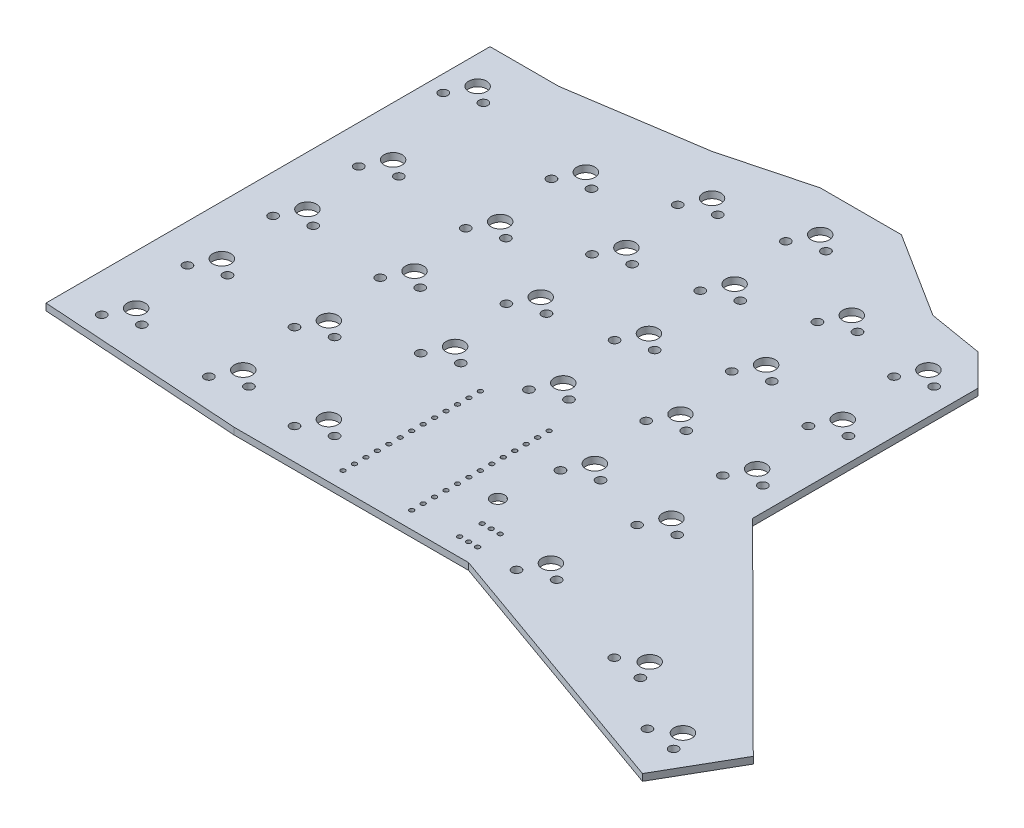
SolidWorks part; units mm, degrees
ref_plane "Front Plane" through (0, 0, 0) normal (0, 0, 1) x (1, 0, 0)
ref_plane "Top Plane" through (0, 0, 0) normal (0, 1, 0) x (1, 0, 0)
ref_plane "Right Plane" through (0, 0, 0) normal (1, 0, 0) x (0, 0, -1)
sketch "Main" plane through (0, 0, 0) normal (0, 1, 0) x (1, 0, 0)
  line L0 (6.46, 3.92) -> (12.81, 6.46) construction
  line L1 (0, 0) -> (18, 0) construction
  line L2 (0, 0) -> (0, 18) construction
  line L3 (0, 18) -> (18, 18) construction
  line L4 (18, 0) -> (18, 18) construction
  line L5 (2, 16) -> (16, 16)
  line L6 (2, 16) -> (2, 2)
  line L7 (2, 2) -> (16, 2)
  line L8 (16, 16) -> (16, 2)
  line L18 (9, 9) -> (6.46, 3.92) construction
  line L20 (9, 9) -> (12.81, 6.46) construction
  line L22 (25.46, 12.92) -> (31.81, 15.46) construction
  line L23 (19, 9) -> (37, 9) construction
  line L24 (19, 9) -> (19, 27) construction
  line L25 (19, 27) -> (37, 27) construction
  line L26 (37, 9) -> (37, 27) construction
  line L27 (21, 25) -> (35, 25)
  line L28 (21, 25) -> (21, 11)
  line L29 (21, 11) -> (35, 11)
  line L30 (35, 25) -> (35, 11)
  line L31 (28, 18) -> (25.46, 12.92) construction
  line L32 (28, 18) -> (31.81, 15.46) construction
  line L33 (44.46, 17.92) -> (50.81, 20.46) construction
  line L34 (38, 14) -> (56, 14) construction
  line L35 (38, 14) -> (38, 32) construction
  line L36 (38, 32) -> (56, 32) construction
  line L37 (56, 14) -> (56, 32) construction
  line L38 (40, 30) -> (54, 30)
  line L39 (40, 30) -> (40, 16)
  line L40 (40, 16) -> (54, 16)
  line L41 (54, 30) -> (54, 16)
  line L42 (47, 23) -> (44.46, 17.92) construction
  line L43 (47, 23) -> (50.81, 20.46) construction
  line L44 (63.46, 5.92) -> (69.81, 8.46) construction
  line L45 (57, 2) -> (75, 2) construction
  line L46 (57, 2) -> (57, 20) construction
  line L47 (57, 20) -> (75, 20) construction
  line L48 (75, 2) -> (75, 20) construction
  line L49 (59, 18) -> (73, 18)
  line L50 (59, 18) -> (59, 4)
  line L51 (59, 4) -> (73, 4)
  line L52 (73, 18) -> (73, 4)
  line L53 (66, 11) -> (63.46, 5.92) construction
  line L54 (66, 11) -> (69.81, 8.46) construction
  line L55 (82.46, 3.92) -> (88.81, 6.46) construction
  line L56 (76, 0) -> (94, 0) construction
  line L57 (76, 0) -> (76, 18) construction
  line L58 (76, 18) -> (94, 18) construction
  line L59 (94, 0) -> (94, 18) construction
  line L60 (78, 16) -> (92, 16)
  line L61 (78, 16) -> (78, 2)
  line L62 (78, 2) -> (92, 2)
  line L63 (92, 16) -> (92, 2)
  line L64 (85, 9) -> (82.46, 3.92) construction
  line L65 (85, 9) -> (88.81, 6.46) construction
  line L88 (2, -3) -> (16, -3)
  line L89 (2, -3) -> (2, -17)
  line L90 (2, -17) -> (16, -17)
  line L91 (16, -3) -> (16, -17)
  line L92 (21, 6) -> (35, 6)
  line L93 (21, 6) -> (21, -8)
  line L94 (21, -8) -> (35, -8)
  line L95 (35, 6) -> (35, -8)
  line L96 (40, 11) -> (54, 11)
  line L97 (40, 11) -> (40, -3)
  line L98 (40, -3) -> (54, -3)
  line L99 (54, 11) -> (54, -3)
  line L100 (59, -1) -> (73, -1)
  line L101 (59, -1) -> (59, -15)
  line L102 (59, -15) -> (73, -15)
  line L103 (73, -1) -> (73, -15)
  line L104 (78, -3) -> (92, -3)
  line L105 (78, -3) -> (78, -17)
  line L106 (78, -17) -> (92, -17)
  line L107 (92, -3) -> (92, -17)
  line L116 (6.46, -15.08) -> (12.81, -12.54) construction
  line L117 (0, -19) -> (18, -19) construction
  line L118 (0, -19) -> (0, -1) construction
  line L119 (0, -1) -> (18, -1) construction
  line L120 (18, -19) -> (18, -1) construction
  line L121 (9, -10) -> (6.46, -15.08) construction
  line L122 (9, -10) -> (12.81, -12.54) construction
  line L123 (25.46, -6.08) -> (31.81, -3.54) construction
  line L124 (19, -10) -> (37, -10) construction
  line L125 (19, -10) -> (19, 8) construction
  line L126 (19, 8) -> (37, 8) construction
  line L127 (37, -10) -> (37, 8) construction
  line L128 (28, -1) -> (25.46, -6.08) construction
  line L129 (28, -1) -> (31.81, -3.54) construction
  line L130 (44.46, -1.08) -> (50.81, 1.46) construction
  line L131 (38, -5) -> (56, -5) construction
  line L132 (38, -5) -> (38, 13) construction
  line L133 (38, 13) -> (56, 13) construction
  line L134 (56, -5) -> (56, 13) construction
  line L135 (47, 4) -> (44.46, -1.08) construction
  line L136 (47, 4) -> (50.81, 1.46) construction
  line L137 (63.46, -13.08) -> (69.81, -10.54) construction
  line L138 (57, -17) -> (75, -17) construction
  line L139 (57, -17) -> (57, 1) construction
  line L140 (57, 1) -> (75, 1) construction
  line L141 (75, -17) -> (75, 1) construction
  line L142 (66, -8) -> (63.46, -13.08) construction
  line L143 (66, -8) -> (69.81, -10.54) construction
  line L144 (82.46, -15.08) -> (88.81, -12.54) construction
  line L145 (76, -19) -> (94, -19) construction
  line L146 (76, -19) -> (76, -1) construction
  line L147 (76, -1) -> (94, -1) construction
  line L148 (94, -19) -> (94, -1) construction
  line L149 (85, -10) -> (82.46, -15.08) construction
  line L150 (85, -10) -> (88.81, -12.54) construction
  line L165 (2, -22) -> (16, -22)
  line L166 (2, -22) -> (2, -36)
  line L167 (2, -36) -> (16, -36)
  line L168 (16, -22) -> (16, -36)
  line L169 (21, -13) -> (35, -13)
  line L170 (21, -13) -> (21, -27)
  line L171 (21, -27) -> (35, -27)
  line L172 (35, -13) -> (35, -27)
  line L173 (40, -8) -> (54, -8)
  line L174 (40, -8) -> (40, -22)
  line L175 (40, -22) -> (54, -22)
  line L176 (54, -8) -> (54, -22)
  line L177 (59, -20) -> (73, -20)
  line L178 (59, -20) -> (59, -34)
  line L179 (59, -34) -> (73, -34)
  line L180 (73, -20) -> (73, -34)
  line L181 (78, -22) -> (92, -22)
  line L182 (78, -22) -> (78, -36)
  line L183 (78, -36) -> (92, -36)
  line L184 (92, -22) -> (92, -36)
  line L193 (6.46, -34.08) -> (12.81, -31.54) construction
  line L194 (0, -38) -> (18, -38) construction
  line L195 (0, -38) -> (0, -20) construction
  line L196 (0, -20) -> (18, -20) construction
  line L197 (18, -38) -> (18, -20) construction
  line L198 (9, -29) -> (6.46, -34.08) construction
  line L199 (9, -29) -> (12.81, -31.54) construction
  line L200 (25.46, -25.08) -> (31.81, -22.54) construction
  line L201 (19, -29) -> (37, -29) construction
  line L202 (19, -29) -> (19, -11) construction
  line L203 (19, -11) -> (37, -11) construction
  line L204 (37, -29) -> (37, -11) construction
  line L205 (28, -20) -> (25.46, -25.08) construction
  line L206 (28, -20) -> (31.81, -22.54) construction
  line L207 (44.46, -20.08) -> (50.81, -17.54) construction
  line L208 (38, -24) -> (56, -24) construction
  line L209 (38, -24) -> (38, -6) construction
  line L210 (38, -6) -> (56, -6) construction
  line L211 (56, -24) -> (56, -6) construction
  line L212 (47, -15) -> (44.46, -20.08) construction
  line L213 (47, -15) -> (50.81, -17.54) construction
  line L214 (63.46, -32.08) -> (69.81, -29.54) construction
  line L215 (57, -36) -> (75, -36) construction
  line L216 (57, -36) -> (57, -18) construction
  line L217 (57, -18) -> (75, -18) construction
  line L218 (75, -36) -> (75, -18) construction
  line L219 (66, -27) -> (63.46, -32.08) construction
  line L220 (66, -27) -> (69.81, -29.54) construction
  line L221 (82.46, -34.08) -> (88.81, -31.54) construction
  line L222 (76, -38) -> (94, -38) construction
  line L223 (76, -38) -> (76, -20) construction
  line L224 (76, -20) -> (94, -20) construction
  line L225 (94, -38) -> (94, -20) construction
  line L226 (85, -29) -> (82.46, -34.08) construction
  line L227 (85, -29) -> (88.81, -31.54) construction
  line L242 (2, -41) -> (16, -41)
  line L243 (2, -41) -> (2, -55)
  line L244 (2, -55) -> (16, -55)
  line L245 (16, -41) -> (16, -55)
  line L246 (21, -32) -> (35, -32)
  line L247 (21, -32) -> (21, -46)
  line L248 (21, -46) -> (35, -46)
  line L249 (35, -32) -> (35, -46)
  line L250 (40, -27) -> (54, -27)
  line L251 (40, -27) -> (40, -41)
  line L252 (40, -41) -> (54, -41)
  line L253 (54, -27) -> (54, -41)
  line L254 (59, -39) -> (73, -39)
  line L255 (59, -39) -> (59, -53)
  line L256 (59, -53) -> (73, -53)
  line L257 (73, -39) -> (73, -53)
  line L258 (78, -41) -> (92, -41)
  line L259 (78, -41) -> (78, -55)
  line L260 (78, -55) -> (92, -55)
  line L261 (92, -41) -> (92, -55)
  line L270 (6.46, -53.08) -> (12.81, -50.54) construction
  line L271 (0, -57) -> (18, -57) construction
  line L272 (0, -57) -> (0, -39) construction
  line L273 (0, -39) -> (18, -39) construction
  line L274 (18, -57) -> (18, -39) construction
  line L275 (9, -48) -> (6.46, -53.08) construction
  line L276 (9, -48) -> (12.81, -50.54) construction
  line L277 (25.46, -44.08) -> (31.81, -41.54) construction
  line L278 (19, -48) -> (37, -48) construction
  line L279 (19, -48) -> (19, -30) construction
  line L280 (19, -30) -> (37, -30) construction
  line L281 (37, -48) -> (37, -30) construction
  line L282 (28, -39) -> (25.46, -44.08) construction
  line L283 (28, -39) -> (31.81, -41.54) construction
  line L284 (44.46, -39.08) -> (50.81, -36.54) construction
  line L285 (38, -43) -> (56, -43) construction
  line L286 (38, -43) -> (38, -25) construction
  line L287 (38, -25) -> (56, -25) construction
  line L288 (56, -43) -> (56, -25) construction
  line L289 (47, -34) -> (44.46, -39.08) construction
  line L290 (47, -34) -> (50.81, -36.54) construction
  line L291 (63.46, -51.08) -> (69.81, -48.54) construction
  line L292 (57, -55) -> (75, -55) construction
  line L293 (57, -55) -> (57, -37) construction
  line L294 (57, -37) -> (75, -37) construction
  line L295 (75, -55) -> (75, -37) construction
  line L296 (66, -46) -> (63.46, -51.08) construction
  line L297 (66, -46) -> (69.81, -48.54) construction
  line L298 (82.46, -53.08) -> (88.81, -50.54) construction
  line L299 (76, -57) -> (94, -57) construction
  line L300 (76, -57) -> (76, -39) construction
  line L301 (76, -39) -> (94, -39) construction
  line L302 (94, -57) -> (94, -39) construction
  line L303 (85, -48) -> (82.46, -53.08) construction
  line L304 (85, -48) -> (88.81, -50.54) construction
  line L312 (6.46, -72.08) -> (12.81, -69.54) construction
  line L313 (0, -76) -> (18, -76) construction
  line L314 (0, -76) -> (0, -58) construction
  line L315 (0, -58) -> (18, -58) construction
  line L316 (18, -76) -> (18, -58) construction
  line L317 (2, -60) -> (16, -60)
  line L318 (2, -60) -> (2, -74)
  line L323 (21, -60) -> (35, -60)
  line L324 (21, -60) -> (21, -74)
  line L325 (21, -74) -> (35, -74)
  line L326 (35, -60) -> (35, -74)
  line L327 (25.46, -72.08) -> (31.81, -69.54) construction
  line L328 (19, -76) -> (37, -76) construction
  line L329 (19, -76) -> (19, -58) construction
  line L330 (-22.04, 8.42) -> (-15.69, 10.96) construction
  line L331 (-28.5, 4.5) -> (-10.5, 4.5) construction
  line L332 (-28.5, 4.5) -> (-28.5, 22.5) construction
  line L333 (-28.5, 22.5) -> (-10.5, 22.5) construction
  line L334 (-10.5, 4.5) -> (-10.5, 22.5) construction
  line L335 (-26.5, 20.5) -> (-12.5, 20.5)
  line L336 (-26.5, 20.5) -> (-26.5, 6.5)
  line L337 (-26.5, 6.5) -> (-12.5, 6.5)
  line L338 (-12.5, 20.5) -> (-12.5, 6.5)
  line L339 (-19.5, 13.5) -> (-22.04, 8.42) construction
  line L340 (-19.5, 13.5) -> (-15.69, 10.96) construction
  line L341 (-21.75, -41) -> (-7.75, -41)
  line L342 (-21.75, -41) -> (-21.75, -55)
  line L343 (-21.75, -55) -> (-7.75, -55)
  line L344 (-7.75, -41) -> (-7.75, -55)
  line L345 (-17.29, -53.08) -> (-10.94, -50.54) construction
  line L346 (-28.5, -57) -> (-1, -57) construction
  line L347 (-28.5, -57) -> (-28.5, -39) construction
  line L348 (-28.5, -39) -> (-1, -39) construction
  line L349 (-1, -57) -> (-1, -39) construction
  line L350 (-14.75, -48) -> (-17.29, -53.08) construction
  line L351 (-14.75, -48) -> (-10.94, -50.54) construction
  line L352 (-21.75, -22) -> (-7.75, -22)
  line L353 (-21.75, -22) -> (-21.75, -36)
  line L354 (2, -74) -> (16, -74)
  line L355 (16, -60) -> (16, -74)
  line L356 (9, -67) -> (6.46, -72.08) construction
  line L357 (9, -67) -> (12.81, -69.54) construction
  line L358 (-17.29, -72.08) -> (-10.94, -69.54) construction
  line L359 (-28.5, -76) -> (-1, -76) construction
  line L360 (-28.5, -76) -> (-28.5, -58) construction
  line L361 (-28.5, -58) -> (-1, -58) construction
  line L362 (-1, -76) -> (-1, -58) construction
  line L363 (-21.75, -60) -> (-7.75, -60)
  line L364 (-21.75, -60) -> (-21.75, -74)
  line L365 (-21.75, -74) -> (-7.75, -74)
  line L366 (-7.75, -60) -> (-7.75, -74)
  line L367 (-14.75, -67) -> (-17.29, -72.08) construction
  line L368 (-14.75, -67) -> (-10.94, -69.54) construction
  line L369 (-21.75, -36) -> (-7.75, -36)
  line L370 (-7.75, -22) -> (-7.75, -36)
  line L371 (-17.29, -34.08) -> (-10.94, -31.54) construction
  line L372 (-28.5, -38) -> (-1, -38) construction
  line L373 (-28.5, -38) -> (-28.5, -20) construction
  line L374 (-28.5, -20) -> (-1, -20) construction
  line L375 (-1, -38) -> (-1, -20) construction
  line L376 (-14.75, -29) -> (-17.29, -34.08) construction
  line L377 (-14.75, -29) -> (-10.94, -31.54) construction
  line L378 (-21.75, -3) -> (-7.75, -3)
  line L379 (-21.75, -3) -> (-21.75, -17)
  line L380 (-21.75, -17) -> (-7.75, -17)
  line L381 (-7.75, -3) -> (-7.75, -17)
  line L382 (-17.29, -15.08) -> (-10.94, -12.54) construction
  line L383 (-28.5, -19) -> (-1, -19) construction
  line L384 (-28.5, -19) -> (-28.5, -1) construction
  line L385 (-28.5, -1) -> (-1, -1) construction
  line L386 (-1, -19) -> (-1, -1) construction
  line L387 (-14.75, -10) -> (-17.29, -15.08) construction
  line L388 (-14.75, -10) -> (-10.94, -12.54) construction
  line L393 (109.2068, -61.578) -> (124.8116, -70.5498) construction
  line L394 (109.2068, -61.578) -> (95.5, -85.4186) construction
  line L398 (124.8116, -70.5498) -> (111.1047, -94.3903) construction
  line L402 (77.71, -75.08) -> (84.06, -72.54) construction
  line L403 (66.5, -79) -> (94, -79) construction
  line L404 (66.5, -79) -> (66.5, -61) construction
  line L405 (66.5, -61) -> (94, -61) construction
  line L406 (94, -79) -> (94, -61) construction
  line L407 (73.25, -63) -> (87.25, -63)
  line L408 (73.25, -63) -> (73.25, -77)
  line L409 (73.25, -77) -> (87.25, -77)
  line L410 (87.25, -63) -> (87.25, -77)
  line L411 (80.25, -70) -> (77.71, -75.08) construction
  line L412 (80.25, -70) -> (84.06, -72.54) construction
  line L413 (95.5, -85.4186) -> (111.1047, -94.3903) construction
  line L414 (95.5, -85.4186) -> (124.8116, -70.5498) construction
  line L415 (80.25, -130) -> (110.1558, -77.9842) construction
  line L416 (107.5763, -68.4267) -> (119.7133, -75.4047)
  line L417 (107.5763, -68.4267) -> (100.5983, -80.5637)
  line L418 (119.7133, -75.4047) -> (112.7353, -87.5417)
  line L419 (100.5983, -80.5637) -> (112.7353, -87.5417)
  line L420 (107.5763, -68.4267) -> (112.7353, -87.5417) construction
  line L421 (105.4217, -81.1221) -> (110.1558, -77.9842) construction
  line L422 (110.1558, -77.9842) -> (112.1927, -82.0853) construction
  line L423 (112.1927, -82.0853) -> (105.4217, -81.1221) construction
  line L424 (126.5454, -71.5466) -> (142.1502, -80.5184) construction
  line L425 (126.5454, -71.5466) -> (112.8386, -95.3872) construction
  line L426 (142.1502, -80.5184) -> (128.4433, -104.3589) construction
  line L427 (112.8386, -95.3872) -> (128.4433, -104.3589) construction
  line L428 (112.8386, -95.3872) -> (142.1502, -80.5184) construction
  line L430 (124.9149, -78.3953) -> (137.0519, -85.3733)
  line L431 (124.9149, -78.3953) -> (117.9369, -90.5323)
  line L432 (137.0519, -85.3733) -> (130.0739, -97.5103)
  line L433 (117.9369, -90.5323) -> (130.0739, -97.5103)
  line L434 (124.9149, -78.3953) -> (130.0739, -97.5103) construction
  line L435 (122.7603, -91.0907) -> (127.4944, -87.9528) construction
  line L436 (127.4944, -87.9528) -> (129.5313, -92.0539) construction
  line L437 (129.5313, -92.0539) -> (122.7603, -91.0907) construction
  line L448 (19, -58) -> (37, -58) construction
  line L449 (37, -76) -> (37, -58) construction
  line L450 (28, -67) -> (25.46, -72.08) construction
  line L451 (28, -67) -> (31.81, -69.54) construction
  circle A0 centre (9, 9) radius 2 construction
  circle A1 centre (6.46, 3.92) radius 1.5 construction
  circle A2 centre (12.81, 6.46) radius 1.5 construction
  circle A6 centre (28, 18) radius 2 construction
  circle A7 centre (25.46, 12.92) radius 1.5 construction
  circle A8 centre (31.81, 15.46) radius 1.5 construction
  circle A9 centre (47, 23) radius 2 construction
  circle A10 centre (44.46, 17.92) radius 1.5 construction
  circle A11 centre (50.81, 20.46) radius 1.5 construction
  circle A12 centre (66, 11) radius 2 construction
  circle A13 centre (63.46, 5.92) radius 1.5 construction
  circle A14 centre (69.81, 8.46) radius 1.5 construction
  circle A15 centre (85, 9) radius 2 construction
  circle A16 centre (82.46, 3.92) radius 1.5 construction
  circle A17 centre (88.81, 6.46) radius 1.5 construction
  circle A24 centre (9, -10) radius 2 construction
  circle A25 centre (6.46, -15.08) radius 1.5 construction
  circle A26 centre (12.81, -12.54) radius 1.5 construction
  circle A27 centre (28, -1) radius 2 construction
  circle A28 centre (25.46, -6.08) radius 1.5 construction
  circle A29 centre (31.81, -3.54) radius 1.5 construction
  circle A30 centre (47, 4) radius 2 construction
  circle A31 centre (44.46, -1.08) radius 1.5 construction
  circle A32 centre (50.81, 1.46) radius 1.5 construction
  circle A33 centre (66, -8) radius 2 construction
  circle A34 centre (63.46, -13.08) radius 1.5 construction
  circle A35 centre (69.81, -10.54) radius 1.5 construction
  circle A36 centre (85, -10) radius 2 construction
  circle A37 centre (82.46, -15.08) radius 1.5 construction
  circle A38 centre (88.81, -12.54) radius 1.5 construction
  circle A45 centre (9, -29) radius 2 construction
  circle A46 centre (6.46, -34.08) radius 1.5 construction
  circle A47 centre (12.81, -31.54) radius 1.5 construction
  circle A48 centre (28, -20) radius 2 construction
  circle A49 centre (25.46, -25.08) radius 1.5 construction
  circle A50 centre (31.81, -22.54) radius 1.5 construction
  circle A51 centre (47, -15) radius 2 construction
  circle A52 centre (44.46, -20.08) radius 1.5 construction
  circle A53 centre (50.81, -17.54) radius 1.5 construction
  circle A54 centre (66, -27) radius 2 construction
  circle A55 centre (63.46, -32.08) radius 1.5 construction
  circle A56 centre (69.81, -29.54) radius 1.5 construction
  circle A57 centre (85, -29) radius 2 construction
  circle A58 centre (82.46, -34.08) radius 1.5 construction
  circle A59 centre (88.81, -31.54) radius 1.5 construction
  circle A63 centre (9, -67) radius 2 construction
  circle A64 centre (6.46, -72.08) radius 1.5 construction
  circle A65 centre (12.81, -69.54) radius 1.5 construction
  circle A66 centre (9, -48) radius 2 construction
  circle A67 centre (6.46, -53.08) radius 1.5 construction
  circle A68 centre (12.81, -50.54) radius 1.5 construction
  circle A69 centre (28, -39) radius 2 construction
  circle A70 centre (25.46, -44.08) radius 1.5 construction
  circle A71 centre (31.81, -41.54) radius 1.5 construction
  circle A72 centre (47, -34) radius 2 construction
  circle A73 centre (44.46, -39.08) radius 1.5 construction
  circle A74 centre (50.81, -36.54) radius 1.5 construction
  circle A75 centre (66, -46) radius 2 construction
  circle A76 centre (63.46, -51.08) radius 1.5 construction
  circle A77 centre (69.81, -48.54) radius 1.5 construction
  circle A78 centre (85, -48) radius 2 construction
  circle A79 centre (82.46, -53.08) radius 1.5 construction
  circle A80 centre (88.81, -50.54) radius 1.5 construction
  circle A81 centre (-14.75, -67) radius 2 construction
  circle A82 centre (-17.29, -72.08) radius 1.5 construction
  circle A83 centre (-10.94, -69.54) radius 1.5 construction
  circle A84 centre (28, -67) radius 2 construction
  circle A85 centre (25.46, -72.08) radius 1.5 construction
  circle A86 centre (31.81, -69.54) radius 1.5 construction
  circle A87 centre (-19.5, 13.5) radius 2 construction
  circle A88 centre (-22.04, 8.42) radius 1.5 construction
  circle A89 centre (-15.69, 10.96) radius 1.5 construction
  circle A90 centre (-14.75, -48) radius 2 construction
  circle A91 centre (-17.29, -53.08) radius 1.5 construction
  circle A92 centre (-10.94, -50.54) radius 1.5 construction
  circle A93 centre (-14.75, -29) radius 2 construction
  circle A94 centre (-17.29, -34.08) radius 1.5 construction
  circle A95 centre (-10.94, -31.54) radius 1.5 construction
  circle A96 centre (-14.75, -10) radius 2 construction
  circle A97 centre (-17.29, -15.08) radius 1.5 construction
  circle A98 centre (-10.94, -12.54) radius 1.5 construction
  circle A102 centre (80.25, -70) radius 2 construction
  circle A103 centre (77.71, -75.08) radius 1.5 construction
  circle A104 centre (84.06, -72.54) radius 1.5 construction
  circle A105 centre (80.25, -130) radius 60 construction
  circle A106 centre (110.1558, -77.9842) radius 2 construction
  circle A107 centre (105.4217, -81.1221) radius 1.5 construction
  circle A108 centre (112.1927, -82.0853) radius 1.5 construction
  circle A109 centre (127.4944, -87.9528) radius 2 construction
  circle A110 centre (122.7603, -91.0907) radius 1.5 construction
  circle A111 centre (129.5313, -92.0539) radius 1.5 construction
  point P9 (9, 16)
  point P10 (9, 18)
  point P11 (2, 9)
  point P12 (0, 9)
  point P30 (28, 25)
  point P31 (28, 27)
  point P32 (21, 18)
  point P33 (19, 18)
  point P46 (47, 30)
  point P47 (47, 32)
  point P48 (40, 23)
  point P49 (38, 23)
  point P64 (66, 18)
  point P65 (66, 20)
  point P66 (59, 11)
  point P67 (57, 11)
  point P82 (85, 16)
  point P83 (85, 18)
  point P84 (78, 9)
  point P85 (76, 9)
  point P102 (9, -60)
  point P103 (9, -58)
  point P104 (2, -67)
  point P105 (0, -67)
  point P124 (-14.75, -60)
  point P125 (-14.75, -58)
  point P126 (-21.75, -67)
  point P127 (-28.5, -67)
  point P297 (-19.5, 20.5)
  point P298 (-19.5, 22.5)
  point P299 (-26.5, 13.5)
  point P300 (-28.5, 13.5)
  point P423 (103.3024, -89.9045)
  point P444 (80.25, -63)
  point P445 (80.25, -61)
  point P446 (73.25, -70)
  point P447 (66.5, -70)
  dimension "D6" = 4
  dimension "D7" = 3
  dimension "D10" = 1
  dimension "D11" = 12
  dimension "D21" = 9.5
  dimension "D22" = 1.5
  dimension "D26" = 120
  dimension "D38" = 21.8
  dimension "D1" = 18
  dimension "D2" = 14
  dimension "D3" = 3.81
  dimension "D4" = 2.54
  dimension "D5" = 2.54
  dimension "D8" = 1
  dimension "D9" = 5
  dimension "D12" = 1
  dimension "D13" = 9
  dimension "D14" = 1
  dimension "D15" = 2
  dimension "D16" = 2
  dimension "D17" = 27.5
  dimension "D18" = 1
  dimension "D20" = 1
  dimension "D24" = 1
  dimension "D25" = 8
  dimension "D27" = 2
  dimension "D28" = 5.08
  dimension "D29" = 2.54
  dimension "D30" = 2.54
  dimension "D31" = 2.54
  dimension "D32" = 2.54
  dimension "D33" = 2.54
  dimension "D34" = 2.54
  dimension "D35" = 2.54
  dimension "D36" = 2.54
  dimension "D37" = 21.8
  dimension "D19" = 4
  dimension "D23" = 4
sketch "Sketch1" plane through (0, 0, 0) normal (0, 1, 0) x (1, 0, 0)
  line L7 (87, 18) -> (94, 11)
  line L8 (115.2061, -91.2693) -> (124.1779, -75.6645) construction
  line L9 (76, 18) -> (94, 18) construction
  line L10 (94, 0) -> (94, 18) construction
  line L11 (66.5, -79) -> (94, -79) construction
  line L12 (115.2061, -91.2693) -> (130.8109, -100.241) construction
  line L14 (124.1779, -75.6645) -> (139.7826, -84.6363) construction
  line L18 (130.8109, -100.241) -> (139.7826, -84.6363)
  line L19 (115.2061, -91.2693) -> (139.7826, -84.6363) construction
  line L20 (124.1779, -75.6645) -> (130.8109, -100.241) construction
  line L23 (142.1502, -80.5184) -> (128.4433, -104.3589) construction
  line L27 (71, -79) -> (130.8109, -100.241)
  line L28 (139.7826, -84.6363) -> (94, -39)
  line L29 (94, -39) -> (94, 11)
  line L30 (87, 18) -> (75, 20)
  line L31 (75, 20) -> (56, 32)
  line L32 (56, 32) -> (38, 32)
  line L33 (38, 32) -> (19, 27)
  line L34 (19, 27) -> (-10.5, 22.5)
  line L35 (-10.5, 22.5) -> (-25.75, 22.5)
  line L38 (19, -79) -> (71, -79)
  line L167 (19, -76) -> (19, -58) construction
  line L168 (75, -55) -> (75, -37) construction
  line L169 (-28.5, -76) -> (-1, -76) construction
  line L174 (-23.75, -58) -> (-5.75, -58) construction
  line L175 (-23.75, -58) -> (-23.75, -76) construction
  line L176 (-23.75, -76) -> (-5.75, -76) construction
  line L177 (-5.75, -58) -> (-5.75, -76) construction
  line L178 (-23.75, -58) -> (-5.75, -76) construction
  line L179 (-23.75, -76) -> (-5.75, -58) construction
  line L181 (19, -79) -> (-25.75, -76)
  line L182 (-25.75, -76) -> (-25.75, 22.5)
  point P1 (127.4944, -87.9528)
  point P24 (-14.75, -67)
  dimension "D2" = 98.5203
  dimension "D7" = 64.643
  dimension "D8" = 7
  dimension "D3" = 42.8551
  dimension "D4" = 52
  dimension "D5" = 63.4706
  dimension "D6" = 18
  dimension "D9" = 7
  dimension "D10" = 22.4722
  dimension "D11" = 18
  dimension "D12" = 19.6469
  dimension "D13" = 29.8412
  dimension "D14" = 15.25
  dimension "D15" = 4
  dimension "D17" = 11
extrude "Main_plate" add sketch "Sketch1" against normal blind 1.5
sketch "Sketch3" plane through (0, 0, 0) normal (0, 1, 0) x (1, 0, 0)
  line L0 (80.25, -70) -> (77.71, -75.08) construction
  line L1 (112.8386, -95.3872) -> (142.1502, -80.5184) construction
  circle A0 centre (-19.5, 13.5) radius 2
  circle A1 centre (9, 9) radius 2
  circle A2 centre (28, 18) radius 2
  circle A3 centre (47, 23) radius 2
  circle A4 centre (66, 11) radius 2
  circle A5 centre (85, 9) radius 2
  circle A6 centre (-14.75, -10) radius 2
  circle A7 centre (9, -10) radius 2
  circle A8 centre (28, -1) radius 2
  circle A9 centre (47, 4) radius 2
  circle A10 centre (66, -8) radius 2
  circle A11 centre (85, -10) radius 2
  circle A12 centre (47, -15) radius 2
  circle A13 centre (-14.75, -29) radius 2
  circle A14 centre (-14.75, -48) radius 2
  circle A15 centre (-14.75, -67) radius 2
  circle A16 centre (9, -29) radius 2
  circle A17 centre (9, -48) radius 2
  circle A18 centre (9, -67) radius 2
  circle A19 centre (28, -67) radius 2
  circle A20 centre (28, -39) radius 2
  circle A21 centre (28, -20) radius 2
  circle A22 centre (47, -34) radius 2
  circle A23 centre (66, -27) radius 2
  circle A24 centre (85, -29) radius 2
  circle A25 centre (85, -48) radius 2
  circle A26 centre (66, -46) radius 2
  circle A27 centre (80.25, -70) radius 2
  circle A28 centre (110.1558, -77.9842) radius 2
  circle A29 centre (127.4944, -87.9528) radius 2
  circle A30 centre (-19.5, 13.5) radius 2 construction
extrude "Switch_holes_main" cut sketch "Sketch3" against normal through all
sketch "Sketch4" plane through (0, 0, 0) normal (0, 1, 0) x (1, 0, 0)
  circle A0 centre (-22.04, 8.42) radius 1
  circle A1 centre (-15.69, 10.96) radius 1
  circle A2 centre (-10.94, -12.54) radius 1
  circle A3 centre (-17.29, -15.08) radius 1
  circle A4 centre (-10.94, -31.54) radius 1
  circle A5 centre (-17.29, -34.08) radius 1
  circle A6 centre (-10.94, -50.54) radius 1
  circle A7 centre (-17.29, -53.08) radius 1
  circle A8 centre (-17.29, -72.08) radius 1
  circle A9 centre (-10.94, -69.54) radius 1
  circle A10 centre (6.46, -72.08) radius 1
  circle A11 centre (12.81, -69.54) radius 1
  circle A12 centre (25.46, -72.08) radius 1
  circle A13 centre (31.81, -69.54) radius 1
  circle A14 centre (6.46, -53.08) radius 1
  circle A15 centre (12.81, -50.54) radius 1
  circle A16 centre (6.46, -34.08) radius 1
  circle A17 centre (12.81, -31.54) radius 1
  circle A18 centre (25.46, -44.08) radius 1
  circle A19 centre (31.81, -41.54) radius 1
  circle A20 centre (25.46, -25.08) radius 1
  circle A21 centre (31.81, -22.54) radius 1
  circle A22 centre (6.46, -15.08) radius 1
  circle A23 centre (12.81, -12.54) radius 1
  circle A24 centre (6.46, 3.92) radius 1
  circle A25 centre (12.81, 6.46) radius 1
  circle A26 centre (25.46, 12.92) radius 1
  circle A27 centre (31.81, 15.46) radius 1
  circle A28 centre (25.46, -6.08) radius 1
  circle A29 centre (31.81, -3.54) radius 1
  circle A30 centre (44.46, 17.92) radius 1
  circle A31 centre (50.81, 20.46) radius 1
  circle A32 centre (44.46, -1.08) radius 1
  circle A33 centre (50.81, 1.46) radius 1
  circle A34 centre (44.46, -20.08) radius 1
  circle A35 centre (50.81, -17.54) radius 1
  circle A36 centre (44.46, -39.08) radius 1
  circle A37 centre (50.81, -36.54) radius 1
  circle A38 centre (69.81, 8.46) radius 1
  circle A39 centre (63.46, 5.92) radius 1
  circle A40 centre (82.46, 3.92) radius 1
  circle A41 centre (88.81, 6.46) radius 1
  circle A42 centre (69.81, -10.54) radius 1
  circle A43 centre (63.46, -13.08) radius 1
  circle A44 centre (82.46, -15.08) radius 1
  circle A45 centre (88.81, -12.54) radius 1
  circle A46 centre (63.46, -32.08) radius 1
  circle A47 centre (69.81, -29.54) radius 1
  circle A48 centre (63.46, -51.08) radius 1
  circle A49 centre (69.81, -48.54) radius 1
  circle A50 centre (82.46, -34.08) radius 1
  circle A51 centre (88.81, -31.54) radius 1
  circle A52 centre (88.81, -50.54) radius 1
  circle A53 centre (82.46, -53.08) radius 1
  circle A54 centre (77.71, -75.08) radius 1
  circle A55 centre (84.06, -72.54) radius 1
  circle A56 centre (105.4217, -81.1221) radius 1
  circle A57 centre (112.1927, -82.0853) radius 1
  circle A58 centre (122.7603, -91.0907) radius 1
  circle A59 centre (129.5313, -92.0539) radius 1
  dimension "D1" = 2
extrude "Switch_holes" cut sketch "Sketch4" against normal through all
sketch "Sketch2" plane through (0, 0, 0) normal (0, 1, 0) x (1, 0, 0)
  line L0 (47, -34) -> (47, -79) construction
  line L1 (19, -79) -> (71, -79) construction
  circle A0 centre (39.38, -75.25) radius 0.5
  circle A1 centre (39.38, -72.71) radius 0.5
  circle A2 centre (39.38, -70.17) radius 0.5
  circle A3 centre (39.38, -67.63) radius 0.5
  circle A4 centre (39.38, -65.09) radius 0.5
  circle A5 centre (39.38, -62.55) radius 0.5
  circle A6 centre (39.38, -60.01) radius 0.5
  circle A7 centre (39.38, -57.47) radius 0.5
  circle A8 centre (39.38, -54.93) radius 0.5
  circle A9 centre (39.38, -52.39) radius 0.5
  circle A10 centre (39.38, -49.85) radius 0.5
  circle A11 centre (39.38, -47.31) radius 0.5
  circle A12 centre (39.38, -44.77) radius 0.5
  circle A13 centre (54.62, -44.77) radius 0.5
  circle A14 centre (54.62, -47.31) radius 0.5
  circle A15 centre (54.62, -49.85) radius 0.5
  circle A16 centre (54.62, -52.39) radius 0.5
  circle A17 centre (54.62, -54.93) radius 0.5
  circle A18 centre (54.62, -57.47) radius 0.5
  circle A19 centre (54.62, -60.01) radius 0.5
  circle A20 centre (54.62, -62.55) radius 0.5
  circle A21 centre (54.62, -65.09) radius 0.5
  circle A22 centre (54.62, -67.63) radius 0.5
  circle A23 centre (54.62, -70.17) radius 0.5
  circle A24 centre (54.62, -72.71) radius 0.5
  circle A25 centre (54.62, -75.25) radius 0.5
  circle A26 centre (62, -63.5) radius 1.5
  dimension "D2" = 1
  dimension "D8" = 3
  dimension "D1" = 41.25
  dimension "D3" = 7.62
  dimension "D5" = 2.54
  dimension "D6" = 11.75
  dimension "D7" = 7.38
  dimension "D4" = 13
extrude "Nice_nano_holes" cut sketch "Sketch2" against normal through all
sketch "Sketch5" plane through (0, 0, 0) normal (0, 1, 0) x (1, 0, 0)
  line L0 (65, -75) -> (67, -75) construction
  line L1 (67, -75) -> (69, -75) construction
  circle A0 centre (65, -75) radius 0.5
  circle A1 centre (67, -75) radius 0.5
  circle A2 centre (69, -75) radius 0.5
  circle A3 centre (65, -70) radius 0.5
  circle A4 centre (69, -70) radius 0.5
  circle A5 centre (67, -70) radius 0.5
  circle A6 centre (54.62, -75.25) radius 0.5 construction
  point P14 (0, 0)
  point P15 (0, 0)
  point P16 (0, 0)
  point P17 (62.0884, -74.8413)
  dimension "D4" = 10.38
  dimension "D1" = 5
  dimension "D2" = 2
  dimension "D3" = 0.25
extrude "Power_switch_holes" cut sketch "Sketch5" against normal through all
